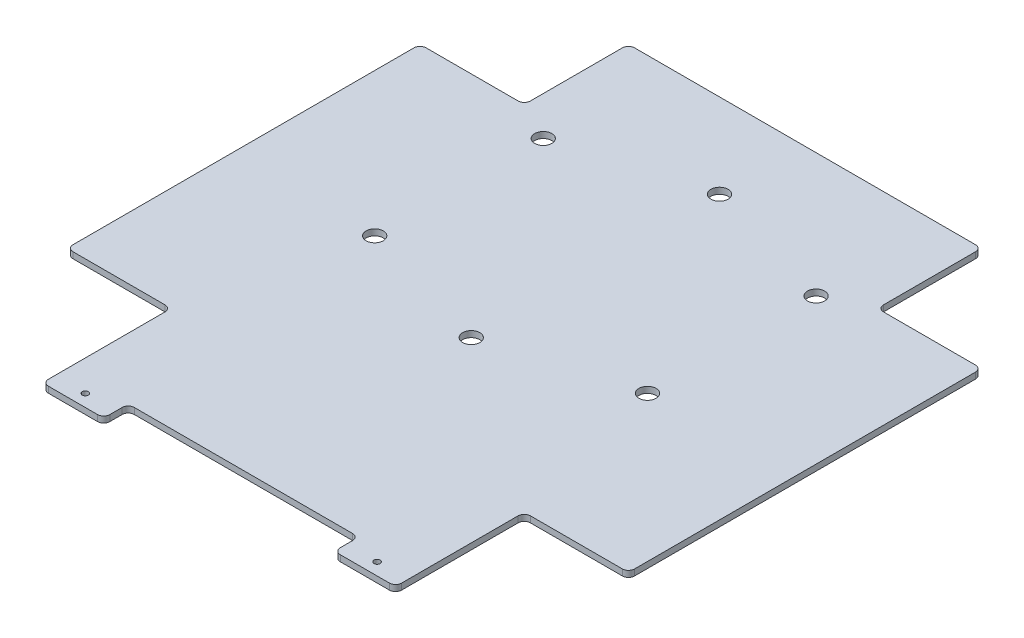
SolidWorks part; units mm, degrees
material "Plain Carbon Steel"
ref_plane "Front Plane" through (0, 0, 0) normal (0, 0, 1) x (1, 0, 0)
ref_plane "Top Plane" through (0, 0, 0) normal (0, 1, 0) x (1, 0, 0)
ref_plane "Right Plane" through (0, 0, 0) normal (1, 0, 0) x (0, 0, -1)
sketch "Sketch1" plane through (0, 0, 0) normal (0, 1, 0) x (1, 0, 0)
  line L1 (-229, 229) -> (229, 229)
  line L2 (-229, 229) -> (-229, -229)
  line L3 (-229, -229) -> (229, -229)
  line L4 (229, 229) -> (229, -229)
  line L5 (-229, 229) -> (229, -229) construction
  line L6 (-229, -229) -> (229, 229) construction
  point P0 (0, 0)
  dimension "D1" = 458
  dimension "D2" = 458
extrude "Boss-Extrude1" add sketch "Sketch1" along normal blind 5
sketch "Sketch2" plane through (0, 5, 0) normal (0, 1, 0) x (1, 0, 0)
  line L1 (-229, 229) -> (-144, 229)
  line L2 (-229, 229) -> (-229, 144)
  line L3 (-229, 144) -> (-144, 144)
  line L4 (-144, 229) -> (-144, 144)
  line L5 (229, 229) -> (144, 229)
  line L6 (229, 229) -> (229, 144)
  line L7 (229, 144) -> (144, 144)
  line L8 (144, 229) -> (144, 144)
  line L9 (229, -229) -> (144, -229)
  line L10 (229, -229) -> (229, -144)
  line L11 (229, -144) -> (144, -144)
  line L12 (144, -229) -> (144, -144)
  line L13 (-229, -229) -> (-144, -229)
  line L14 (-229, -229) -> (-229, -144)
  line L15 (-229, -144) -> (-144, -144)
  line L16 (-144, -229) -> (-144, -144)
  dimension "D1" = 85
  dimension "D2" = 85
  dimension "D3" = 85
  dimension "D4" = 85
extrude "Cut-Extrude1" cut sketch "Sketch2" against normal through all
sketch "Sketch3" plane through (0, 0, 0) normal (0, -1, 0) x (1, 0, 0)
  circle A0 centre (-112.25, 9.75) radius 7
  circle A1 centre (-112.25, -127.75) radius 7
  circle A2 centre (-1, -160.25) radius 7
  circle A3 centre (110.25, -127.75) radius 7
  circle A4 centre (110.25, 9.75) radius 7
  circle A5 centre (-1, 42.25) radius 7
  dimension "D1" = 14
sketch "Sketch4" plane through (0, 5, 0) normal (0, 1, 0) x (1, 0, 0)
  line L1 (-144, -229) -> (-94, -229)
  line L2 (-144, -229) -> (-144, -249)
  line L3 (-144, -249) -> (-94, -249)
  line L4 (-94, -229) -> (-94, -249)
  line L5 (144, -229) -> (94, -229)
  line L6 (144, -229) -> (144, -249)
  line L7 (144, -249) -> (94, -249)
  line L8 (94, -229) -> (94, -249)
  dimension "D1" = 20
  dimension "D2" = 20
  dimension "D3" = 50
  dimension "D4" = 50
extrude "Boss-Extrude2" add sketch "Sketch4" against normal blind 5
fillet "Fillet1" radius 5 6 edges at (-144, 2.5, 144) (144, 2.5, 144) (144, 2.5, -144) (-144, 2.5, -144) (94, 2.5, 229) (-94, 2.5, 229)
fillet "Fillet2" radius 5 10 edges at (94, 2.5, 249) (144, 2.5, 249) (229, 2.5, 144) (229, 2.5, -144) (144, 2.5, -229) (-144, 2.5, -229) (-229, 2.5, -144) (-229, 2.5, 144) (-94, 2.5, 249) (-144, 2.5, 249)
sketch "Sketch5" plane through (0, 5, 0) normal (0, 1, 0) x (1, 0, 0)
  line L0 (-144, -244) -> (-144, -149) construction
  line L1 (-139, -249) -> (-99, -249) construction
  line L2 (99, -249) -> (139, -249) construction
  line L4 (144, -149) -> (144, -244) construction
  point P0 (-119, -239)
  point P1 (119, -239)
  dimension "D1" = 25
  dimension "D2" = 10
  dimension "D3" = 10
  dimension "D4" = 25
hole_wizard "Ø5.0 (5) Diameter Hole1" positions "Sketch6" profile "Sketch7" hole size "Ø5.0" standard "ANSI Metric"
sketch "Sketch6" plane through (0, 5, 0) normal (0, 1, 0) x (1, 0, 0)
  point P0 (-119, -239)
  point P3 (119, -239)
sketch "Sketch7" plane through (-119, 5, 239) normal (1, 0, 0) x (0, 0, 1)
  line L0 (0, 0) -> (0, 39.5022)
  line L1 (0, 39.5022) -> (2.5, 38)
  line L2 (2.5, 38) -> (2.5, 0)
  line L5 (2.5, 0) -> (0, 0)
  line L10 (0, 39.5022) -> (-2.5, 38) construction
  line L11 (0, -6.35) -> (0, 107.95) construction
  dimension "Hole Dia." = 5
  dimension "Hole Depth" = 38
  dimension "Drill Angle" = 118
hole_wizard "Ø14.0 (14) Diameter Hole1" positions "Sketch10" profile "Sketch12" hole size "Ø14.0" standard "ANSI Metric" end condition through all
sketch "Sketch10" plane through (0, 0, 0) normal (0, -1, 0) x (-1, 0, 0)
  point P0 (112.25, 127.75)
  point P3 (112.25, -9.75)
  point P6 (1, 160.25)
  point P9 (-110.25, 127.75)
  point P12 (-110.25, -9.75)
  point P15 (1, -42.25)
sketch "Sketch12" plane through (-112.25, 0, -127.75) normal (1, 0, 0) x (0, 0, -1)
  line L0 (0, 0) -> (0, 5)
  line L1 (0, 5) -> (7, 5)
  line L2 (7, 5) -> (7, 0)
  line L5 (7, 0) -> (0, 0)
  line L11 (0, -6.35) -> (0, 107.95) construction
  dimension "Thru Hole Dia." = 14
  dimension "Thru Hole Depth" = 5
